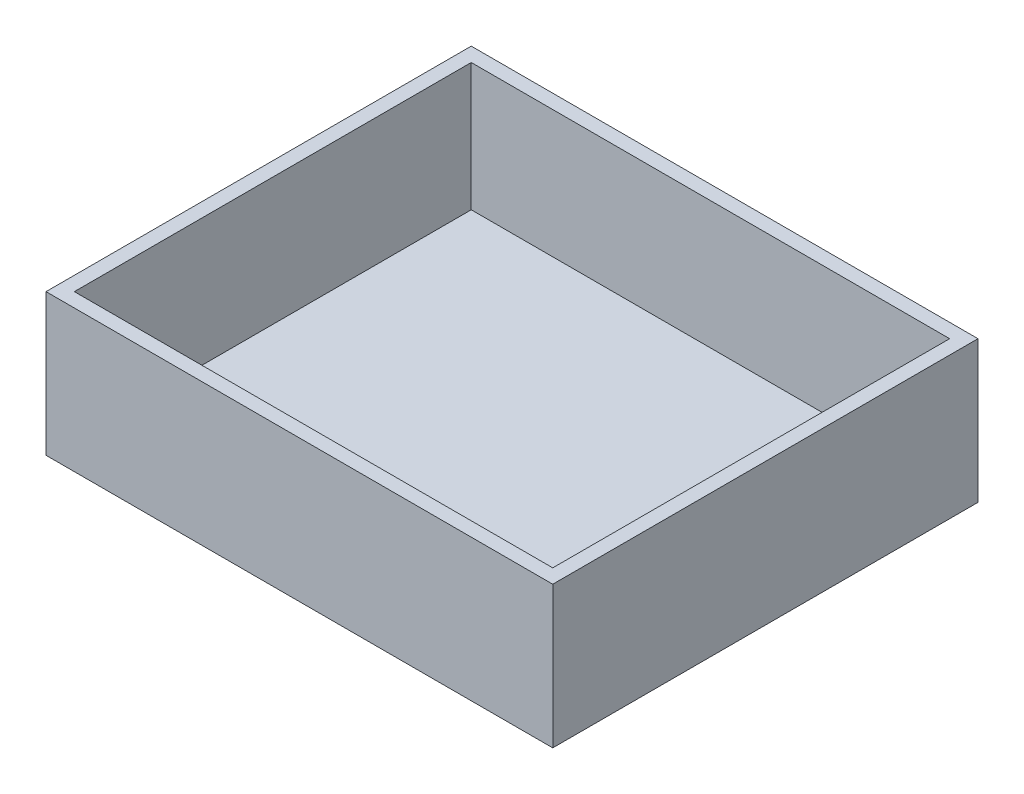
SolidWorks part; units mm, degrees
ref_plane "Alzado" through (0, 0, 0) normal (0, 0, 1) x (1, 0, 0)
ref_plane "Planta" through (0, 0, 0) normal (0, 1, 0) x (1, 0, 0)
ref_plane "Vista lateral" through (0, 0, 0) normal (1, 0, 0) x (0, 0, -1)
sketch "Croquis1" plane through (0, 0, 0) normal (0, 1, 0) x (1, 0, 0)
  line L1 (35.75, -30) -> (-35.75, -30)
  line L2 (35.75, -30) -> (35.75, 30)
  line L3 (35.75, 30) -> (-35.75, 30)
  line L4 (-35.75, -30) -> (-35.75, 30)
  line L5 (35.75, -30) -> (-35.75, 30) construction
  line L6 (35.75, 30) -> (-35.75, -30) construction
  point P0 (0, 0)
  dimension "D1" = 71.5
  dimension "D2" = 60
extrude "Saliente-Extruir1" add sketch "Croquis1" along normal blind 20
shell "Vaciado1" thickness 2
sketch "Croquis3" plane through (0, 0, 0) normal (0, -1, 0) x (1, 0, 0)
  line L0 (-35.75, -30) -> (-35.75, 30) construction
  line L1 (-29.25, 24) -> (3.4503, 24)
  line L2 (-29.25, 24) -> (-29.25, 19.5975)
  line L3 (-29.25, 19.5975) -> (3.4503, 19.5975)
  line L4 (3.4503, 24) -> (3.4503, 19.5975)
  line L5 (-35.75, 30) -> (35.75, 30) construction
  line L6 (35.75, -30) -> (-35.75, -30) construction
  line L7 (-29.25, -19.0577) -> (-0.1371, -19.0577)
  line L8 (-29.25, -19.0577) -> (-29.25, -24)
  line L9 (-29.25, -24) -> (-0.1371, -24)
  line L10 (-0.1371, -19.0577) -> (-0.1371, -24)
  dimension "D1" = 6.5
  dimension "D2" = 6
  dimension "D3" = 6.5
  dimension "D4" = 6
extrude "Saliente-Extruir2" add sketch "Croquis3" along normal blind 3
